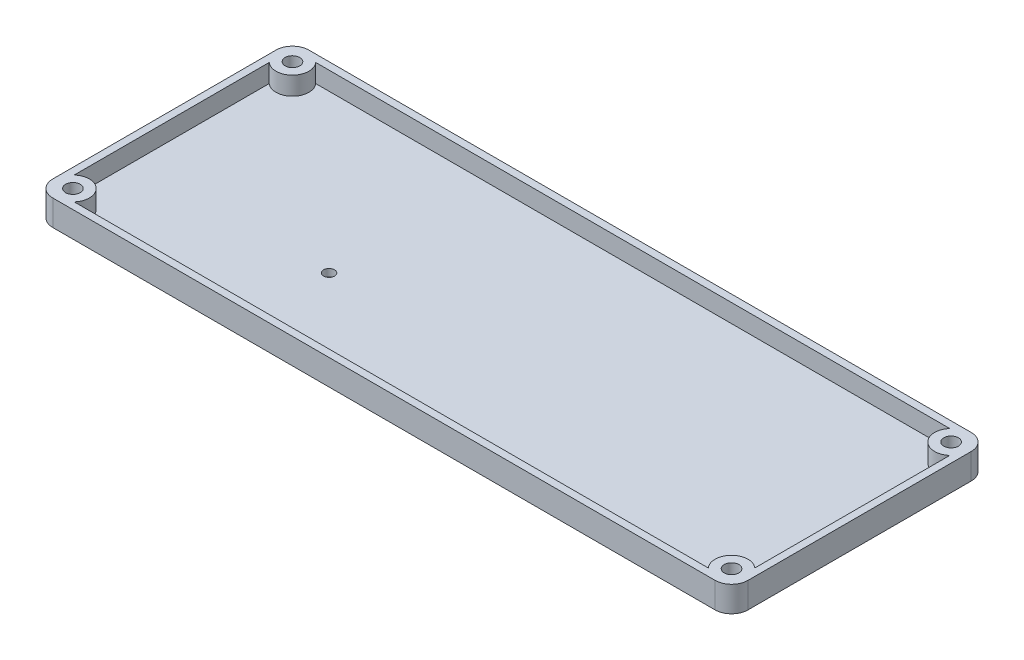
SolidWorks part; units mm, degrees
ref_plane "Front Plane" through (0, 0, 0) normal (0, 0, 1) x (1, 0, 0)
ref_plane "Top Plane" through (0, 0, 0) normal (0, 1, 0) x (1, 0, 0)
ref_plane "Right Plane" through (0, 0, 0) normal (1, 0, 0) x (0, 0, -1)
sketch "Sketch1" plane through (0, 0, 0) normal (0, 1, 0) x (1, 0, 0)
  line L1 (0, 0) -> (190, 0)
  line L2 (0, 0) -> (0, 70)
  line L3 (0, 70) -> (190, 70)
  line L4 (190, 0) -> (190, 70)
  dimension "D1" = 70
  dimension "D2" = 190
extrude "Boss-Extrude1" add sketch "Sketch1" along normal blind 2
sketch "Sketch2" plane through (0, 2, 0) normal (0, 1, 0) x (1, 0, 0)
  line L0 (0, 70) -> (0, 0)
  line L1 (0, 0) -> (190, 0)
  line L3 (190, 70) -> (0, 70)
  line L4 (2, 68) -> (2, 2)
  line L5 (2, 2) -> (188, 2)
  line L6 (190, 0) -> (190, 70)
  line L7 (188, 2) -> (188, 68)
  line L8 (188, 68) -> (2, 68)
  dimension "D1" = 2
  dimension "D2" = 2
  dimension "D3" = 2
  dimension "D4" = 2
extrude "Boss-Extrude2" add sketch "Sketch2" along normal blind 5
sketch "Sketch3" plane through (0, 2, 0) normal (0, 1, 0) x (1, 0, 0)
  line L0 (190, 70) -> (0, 70) construction
  line L1 (0, 70) -> (0, 0) construction
  circle A0 centre (5, 65) radius 4.5
  circle A1 centre (5, 5) radius 4.5
  circle A2 centre (185, 65) radius 4.5
  circle A3 centre (185, 5) radius 4.5
  point P12 (0, 0)
  point P13 (0, 0)
  dimension "D1" = 9
  dimension "D4" = 9
  dimension "D5" = 9
  dimension "D6" = 9
  dimension "D2" = 5
  dimension "D3" = 5
  dimension "D7" = 60
  dimension "D8" = 180
extrude "Boss-Extrude3" add sketch "Sketch3" along normal blind 5
sketch "Sketch4" plane through (0, 7, 0) normal (0, 1, 0) x (1, 0, 0)
  circle A0 centre (5, 65) radius 2
  circle A1 centre (185, 65) radius 2
  circle A2 centre (185, 5) radius 2
  circle A3 centre (5, 5) radius 2
  dimension "D1" = 4
  dimension "D2" = 4
  dimension "D3" = 4
  dimension "D4" = 4
extrude "Cut-Extrude1" cut sketch "Sketch4" against normal blind 14
sketch "Sketch5" plane through (0, 0, 0) normal (0, -1, 0) x (1, 0, 0)
  circle A0 centre (5, -5) radius 3.3
  circle A1 centre (5, -65) radius 3.3
  circle A2 centre (185, -5) radius 3.3
  circle A3 centre (185, -65) radius 3.3
  dimension "D1" = 6.6
  dimension "D2" = 6.6
  dimension "D3" = 6.6
  dimension "D4" = 6.6
extrude "Cut-Extrude2" cut sketch "Sketch5" against normal blind 2.5
fillet "Fillet1" radius 4.5 4 edges at (0, 3.5, 0) (190, 3.5, 0) (190, 3.5, -70) (0, 3.5, -70)
sketch "Sketch6" plane through (0, 0, 0) normal (0, -1, 0) x (1, 0, 0)
  line L0 (0, -65.5) -> (0, -4.5) construction
  line L1 (4.5, 0) -> (185.5, 0) construction
  circle A0 centre (55, -25) radius 1.5
  dimension "D1" = 3
  dimension "D2" = 55
  dimension "D3" = 25
extrude "Cut-Extrude3" cut sketch "Sketch6" against normal blind 2.5
sketch "Sketch7" plane through (0, 0, 0) normal (0, -1, 0) x (1, 0, 0)
  line L1 (60, 0) -> (60, -70) construction
  line L2 (4.5, 0) -> (185.5, 0) construction
  line L3 (185.5, -70) -> (4.5, -70) construction
  line L4 (0, -65.5) -> (0, -4.5) construction
  line L5 (55, -33) -> (53, -35)
  line L10 (53, -35) -> (54, -35)
  line L11 (54, -35) -> (54, -45)
  line L12 (54, -45) -> (56, -45)
  line L13 (56, -45) -> (56, -35)
  line L14 (56, -35) -> (57, -35)
  line L15 (57, -35) -> (55, -33)
  circle A0 centre (55, -25) radius 1.5 construction
  text T0 "Insert Tubing Here" font "@NanumGothic" height 3.5
  point P18 (0, 0)
  point P21 (55, -25)
  dimension "D1" = 60
  dimension "D2" = 2
  dimension "D3" = 1
  dimension "D4" = 1
  dimension "D5" = 2
  dimension "D6" = 20
  dimension "D7" = 10
extrude "Cut-Extrude4" cut sketch "Sketch7" against normal blind 1
